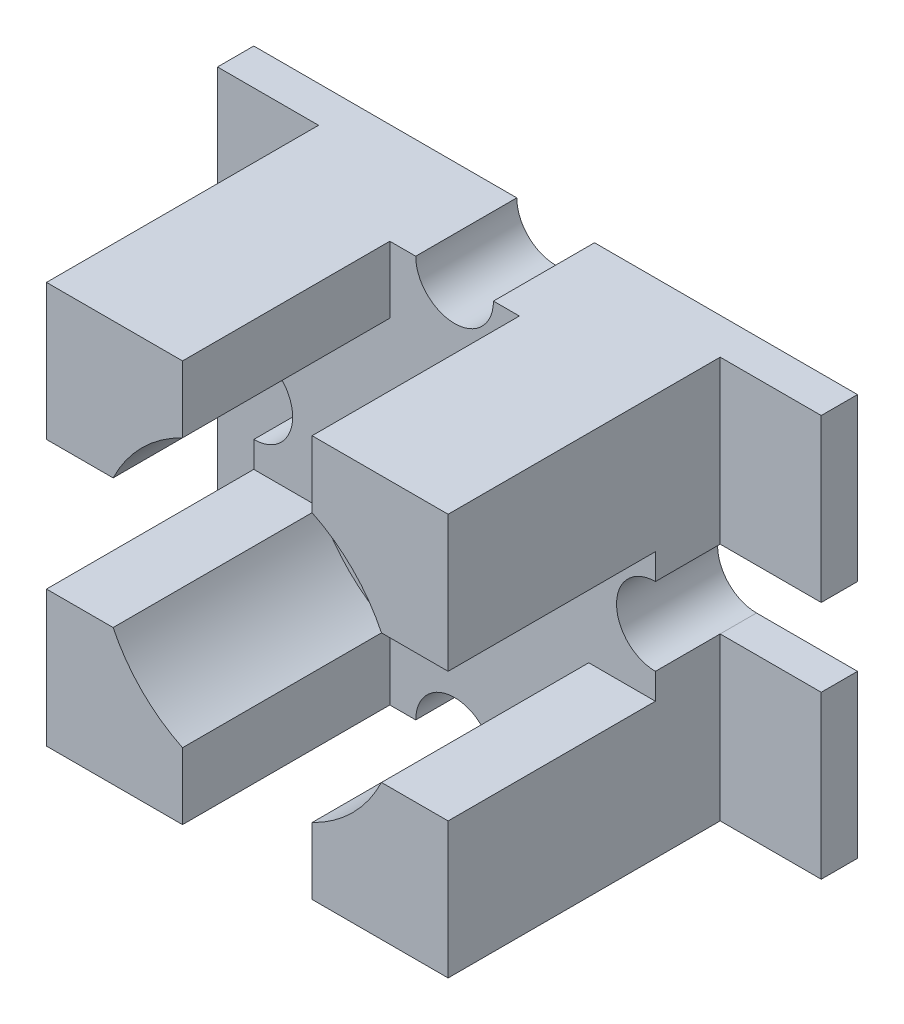
SolidWorks part; units mm, degrees
ref_plane "Front Plane" through (0, 0, 0) normal (0, 0, 1) x (1, 0, 0)
ref_plane "Top Plane" through (0, 0, 0) normal (0, 1, 0) x (1, 0, 0)
ref_plane "Right Plane" through (0, 0, 0) normal (1, 0, 0) x (0, 0, -1)
sketch "Sketch1" plane through (0, 0, 0) normal (0, 0, 1) x (1, 0, 0)
  line L1 (11.65, 7.75) -> (-11.65, 7.75)
  line L2 (11.65, 7.75) -> (11.65, -7.75)
  line L3 (11.65, -7.75) -> (-11.65, -7.75)
  line L4 (-11.65, 7.75) -> (-11.65, -7.75)
  line L5 (11.65, 7.75) -> (-11.65, -7.75) construction
  line L6 (11.65, -7.75) -> (-11.65, 7.75) construction
  point P0 (0, 0)
  dimension "D1" = 23.3
  dimension "D2" = 15.5
extrude "Boss-Extrude1" add sketch "Sketch1" along normal blind 3
sketch "Sketch2" plane through (0, 0, 3) normal (0, 0, 1) x (1, 0, 0)
  line L1 (7.75, 7.75) -> (-7.75, 7.75)
  line L2 (7.75, 7.75) -> (7.75, -7.75)
  line L3 (7.75, -7.75) -> (-7.75, -7.75)
  line L4 (-7.75, 7.75) -> (-7.75, -7.75)
  line L5 (7.75, 7.75) -> (-7.75, -7.75) construction
  line L6 (7.75, -7.75) -> (-7.75, 7.75) construction
  point P0 (0, 0)
  dimension "D1" = 15.5
  dimension "D2" = 15.5
extrude "Boss-Extrude2" add sketch "Sketch2" along normal blind 10.5
sketch "Sketch3" plane through (0, 0, 13.5) normal (0, 0, 1) x (1, 0, 0)
  line L0 (7.75, 7.75) -> (-7.75, 7.75) construction
  line L1 (-2.5, 8.3685) -> (2.5, 8.3685)
  line L2 (-2.5, 8.3685) -> (-2.5, 4.3042)
  line L3 (-2.5, 4.3042) -> (2.5, 4.3042)
  line L4 (2.5, 8.3685) -> (2.5, 4.3042)
  line L5 (8.6588, 2.5) -> (3.9886, 2.5)
  line L6 (8.6588, 2.5) -> (8.6588, -2.5)
  line L7 (8.6588, -2.5) -> (3.9886, -2.5)
  line L8 (3.9886, 2.5) -> (3.9886, -2.5)
  line L9 (-2.5, -8.7977) -> (2.5, -8.7977)
  line L10 (-2.5, -8.7977) -> (-2.5, -3.8245)
  line L11 (-2.5, -3.8245) -> (2.5, -3.8245)
  line L12 (2.5, -8.7977) -> (2.5, -3.8245)
  line L13 (-9.8544, -2.5) -> (-5.1781, -2.5)
  line L14 (-9.8544, -2.5) -> (-9.8544, 2.5)
  line L15 (-9.8544, 2.5) -> (-5.1781, 2.5)
  line L16 (-5.1781, -2.5) -> (-5.1781, 2.5)
  line L17 (-7.75, -7.75) -> (7.75, -7.75) construction
  line L18 (7.75, -7.75) -> (7.75, 7.75) construction
  line L19 (-7.75, 7.75) -> (-7.75, -7.75) construction
  line L20 (-7.75, 7.75) -> (-7.75, -7.75) construction
  circle A0 centre (0, 0) radius 5.75
  line M11 (-7.75, 7.75) -> (-7.75, -7.75)
  line M12 (-7.75, -7.75) -> (7.75, -7.75)
  line M13 (7.75, -7.75) -> (7.75, 7.75)
  line M14 (7.75, 7.75) -> (-7.75, 7.75)
  dimension "D1" = 11.5
  dimension "D2" = 5
  dimension "D3" = 5
  dimension "D4" = 5
  dimension "D5" = 5
  dimension "D6" = 5.25
  dimension "D7" = 5.25
  dimension "D8" = 5.25
  dimension "D9" = 5.25
  dimension "D10" = 5.25
  dimension "D11" = 5.25
extrude "Cut-Extrude1" cut sketch "Sketch3" against normal blind 8 contours L5 A0 L4 L3 L2 L16 L10 L11 L12 L7 L8 | L16 A0 | A0 L15 L13 M11 | L4 A0 L2 L3 | A0 L4 L2 M14 | A0 L7 L5 M13 | L7 A0 L5 L8 | L10 A0 L12 L11 | A0 L10 L12 M12
sketch "Sketch4" plane through (0, 0, 3) normal (0, 0, 1) x (1, 0, 0)
  line L0 (2.5, 7.75) -> (-2.5, 7.75) construction
  line L1 (-2.5, -7.75) -> (2.5, -7.75) construction
  line L2 (7.75, -7.75) -> (7.75, 7.75) construction
  line L3 (-7.75, 7.75) -> (-7.75, -7.75) construction
  line L4 (-7.75, 1.5) -> (-11.65, 1.5)
  line L5 (-11.65, 7.75) -> (-11.65, -7.75) construction
  line L6 (-7.75, -1.5) -> (-11.65, -1.5)
  line L7 (7.75, 1.5) -> (11.65, 1.5)
  line L10 (7.75, -1.5) -> (11.65, -1.5)
  line L13 (11.65, -7.75) -> (11.65, 7.75) construction
  line L14 (-11.65, 7.75) -> (-11.65, -7.75)
  line L15 (11.65, -7.75) -> (11.65, 7.75)
  circle A0 centre (0, 7.75) radius 1.5
  circle A1 centre (0, -7.75) radius 1.5
  circle A2 centre (7.75, 0) radius 1.5
  circle A3 centre (-7.75, 0) radius 1.5
  line M2 (-7.75, -7.75) -> (-7.75, 7.75)
  line M4 (-11.65, 7.75) -> (-11.65, -7.75)
  dimension "D1" = 3
  dimension "D2" = 3
  dimension "D3" = 3
  dimension "D4" = 3
extrude "Cut-Extrude2" cut sketch "Sketch4" against normal blind 3 and the other way blind 10 contours A0 | A2 | A2 L10 L15 L7 | A3 L4 L6 M4 | A3 M2 | A1
sketch "Sketch5" plane through (0, 0, 0) normal (0, 0, -1) x (-1, 0, 0)
  line L1 (-16.012, 10.6073) -> (19.6922, 10.6073)
  line L2 (-16.012, 10.6073) -> (-16.012, -12.6915)
  line L3 (-16.012, -12.6915) -> (19.6922, -12.6915)
  line L4 (19.6922, 10.6073) -> (19.6922, -12.6915)
extrude "Cut-Extrude3" cut sketch "Sketch5" against normal blind 1.6
